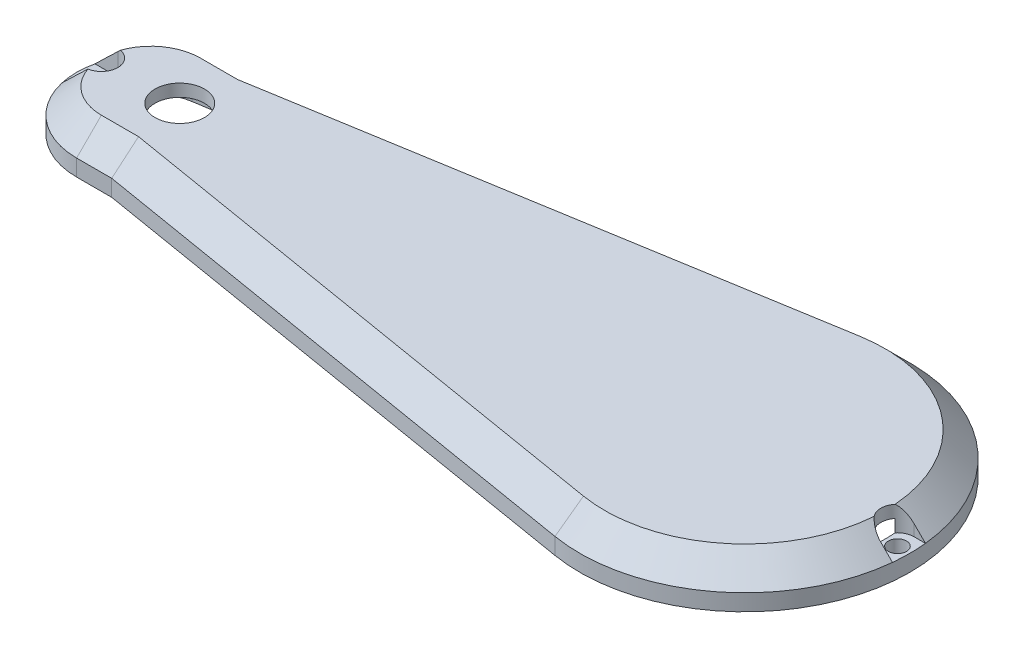
SolidWorks part; units mm, degrees
ref_plane "Front Plane" through (0, 0, 0) normal (0, 0, 1) x (1, 0, 0)
ref_plane "Top Plane" through (0, 0, 0) normal (0, 1, 0) x (1, 0, 0)
ref_plane "Right Plane" through (0, 0, 0) normal (1, 0, 0) x (0, 0, -1)
sketch "Sketch2" plane through (0, 0, 0) normal (0, 1, 0) x (1, 0, 0)
  line L0 (-45.1626, -0.708) -> (55.8374, -0.708) construction
  line L1 (55.8374, -0.708) -> (35.8374, -0.708) construction
  line L2 (-45.1626, -0.708) -> (-36.1626, -0.708) construction
  line L3 (-45.1626, -0.708) -> (-42.1626, -0.708) construction
  line L4 (-36.1626, 8.292) -> (-31.9065, 8.292)
  line L6 (-36.1626, -9.708) -> (-31.9065, -9.708)
  line L8 (55.8374, -0.708) -> (54.3374, -0.708) construction
  line L9 (35.8374, -0.708) -> (-31.1626, -0.708) construction
  line L10 (-31.9065, 8.292) -> (32.5538, 19.0206)
  line L11 (-31.9065, -9.708) -> (32.5538, -20.4366)
  arc A0 (32.5538, -20.4366) -> (32.5538, 19.0206) centre (35.8374, -0.708) ccw
  arc A1 (-36.1626, 8.292) -> (-36.1626, -9.708) centre (-36.1626, -0.708) ccw
  circle A2 centre (-42.1626, -0.708) radius 1.1
  circle A3 centre (54.3374, -0.708) radius 1.1
  circle A4 centre (-31.1626, -0.708) radius 9 construction
  dimension "D6" = 2.2
  dimension "D7" = 2.2
  dimension "D10" = 18
  dimension "D1" = 101
  dimension "D2" = 20
  dimension "D3" = 9
  dimension "D4" = 3
  dimension "D5" = 1.5
  dimension "D8" = 67
  dimension "D9" = 11
extrude "Boss-Extrude1" add sketch "Sketch2" along normal blind 5
sketch "Sketch3" plane through (0, 5, 0) normal (0, 1, 0) x (1, 0, 0)
  line L0 (35.8374, -0.708) -> (-31.1626, -0.708) construction
  line L5 (-45.1626, -0.708) -> (-36.1626, -0.708) construction
  line L6 (-36.1626, 5.292) -> (-31.6585, 5.292)
  line L7 (-31.6585, 5.292) -> (33.0464, 16.0613)
  line L8 (-36.1626, -6.708) -> (-31.6585, -6.708)
  line L9 (-31.6585, -6.708) -> (33.0464, -17.4773)
  arc A0 (33.0464, -17.4773) -> (33.0464, 16.0613) centre (35.8374, -0.708) ccw
  arc A4 (-36.1626, 8.292) -> (-36.1626, -9.708) centre (-36.1626, -0.708) ccw construction
  arc A5 (-36.1626, 5.292) -> (-36.1626, -6.708) centre (-36.1626, -0.708) ccw
  dimension "D1" = 34
  dimension "D2" = 67
  dimension "D4" = 9
  dimension "D5" = 12
extrude "Cut-Extrude1" cut sketch "Sketch3" against normal blind 3 draft 45 flip side to cut
sketch "Sketch4" plane through (0, 5, 0) normal (0, 1, 0) x (1, 0, 0)
  line L1 (-42.1626, 1.292) -> (-47.0361, 1.292)
  line L3 (-42.1626, -2.708) -> (-47.0361, -2.708)
  line L4 (-47.0361, 1.292) -> (-47.0361, -2.708)
  arc A0 (-42.1626, -2.708) -> (-42.1626, 1.292) centre (-42.1626, -0.708) ccw
  dimension "D1" = 4
extrude "Cut-Extrude2" cut sketch "Sketch4" against normal blind 3
sketch "Sketch5" plane through (0, 5, 0) normal (0, 1, 0) x (1, 0, 0)
  line L0 (55.8374, -0.708) -> (54.3374, -0.708) construction
  line L2 (54.3374, 1.292) -> (57.4526, 1.292)
  line L4 (54.3374, -2.708) -> (57.4526, -2.708)
  line L5 (57.4526, 1.292) -> (57.4526, -2.708)
  circle A0 centre (35.8374, -0.708) radius 20 construction
  arc A1 (54.3374, 1.292) -> (54.3374, -2.708) centre (54.3374, -0.708) ccw
  dimension "D1" = 40
  dimension "D3" = 4
  dimension "D2" = 1.5
extrude "Cut-Extrude3" cut sketch "Sketch5" against normal blind 3
sketch "Sketch6" plane through (0, 5, 0) normal (0, 1, 0) x (1, 0, 0)
  line L0 (35.8374, -0.708) -> (-32.6626, -0.708) construction
  circle A0 centre (-32.6626, -0.708) radius 3
  dimension "D2" = 6
  dimension "D1" = 68.5
extrude "Cut-Extrude4" cut sketch "Sketch6" against normal blind 9
sketch "Sketch7" plane through (0, 0, 0) normal (0, -1, 0) x (1, 0, 0)
  line L0 (-37.0793, 6.6376) -> (33.2402, 17.5084)
  line L2 (33.2402, -16.0924) -> (-37.0793, -5.2216)
  arc A0 (33.2402, -16.0924) -> (33.2402, 17.5084) centre (35.8374, 0.708) ccw
  arc A1 (-37.0793, 6.6376) -> (-37.0793, -5.2216) centre (-36.1626, 0.708) ccw
  dimension "D1" = 34
  dimension "D2" = 12
extrude "Cut-Extrude5" cut sketch "Sketch7" against normal blind 3.5
